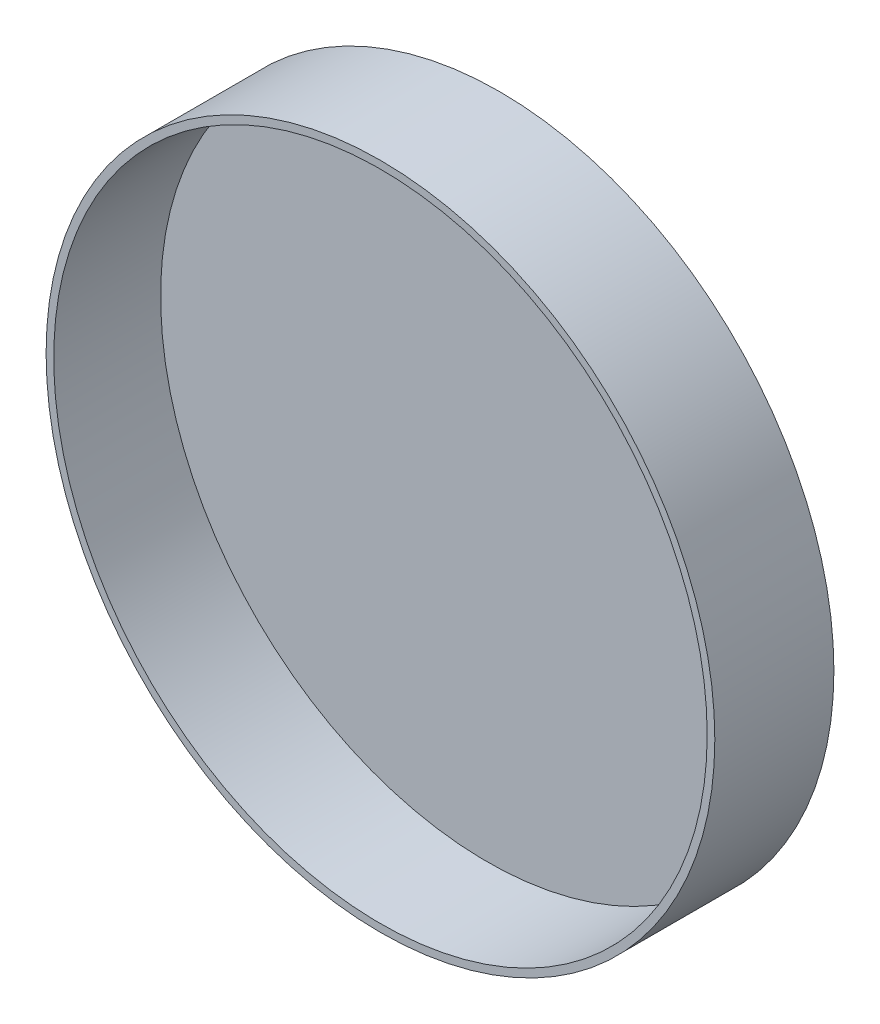
SolidWorks part; units mm, degrees
ref_plane "Front" through (0, 0, 0) normal (0, 0, 1) x (1, 0, 0)
ref_plane "Top" through (0, 0, 0) normal (0, 1, 0) x (1, 0, 0)
ref_plane "Right" through (0, 0, 0) normal (1, 0, 0) x (0, 0, -1)
sketch "Sketch1" plane through (0, 0, 0) normal (0, 0, 1) x (1, 0, 0)
  circle A0 centre (0, 0) radius 21.9
  dimension "D1" = 43.8
extrude "Extrude1" add sketch "Sketch1" along normal blind 0.8
sketch "Sketch2" plane through (0, 0, 0.8) normal (0, 0, 1) x (1, 0, 0)
  circle A0 centre (0, 0) radius 21.9
  circle A1 centre (0, 0) radius 21.4
  dimension "D1" = 43.8
  dimension "D2" = 42.8
extrude "Extrude2" add sketch "Sketch2" along normal blind 7
sketch "Sketch4" plane through (0, 0, 0.8) normal (0, 0, 1) x (1, 0, 0)
  circle A0 centre (0, 0) radius 2
  dimension "D1" = 4
extrude "Extrude4" add sketch "Sketch4" against normal blind 10
